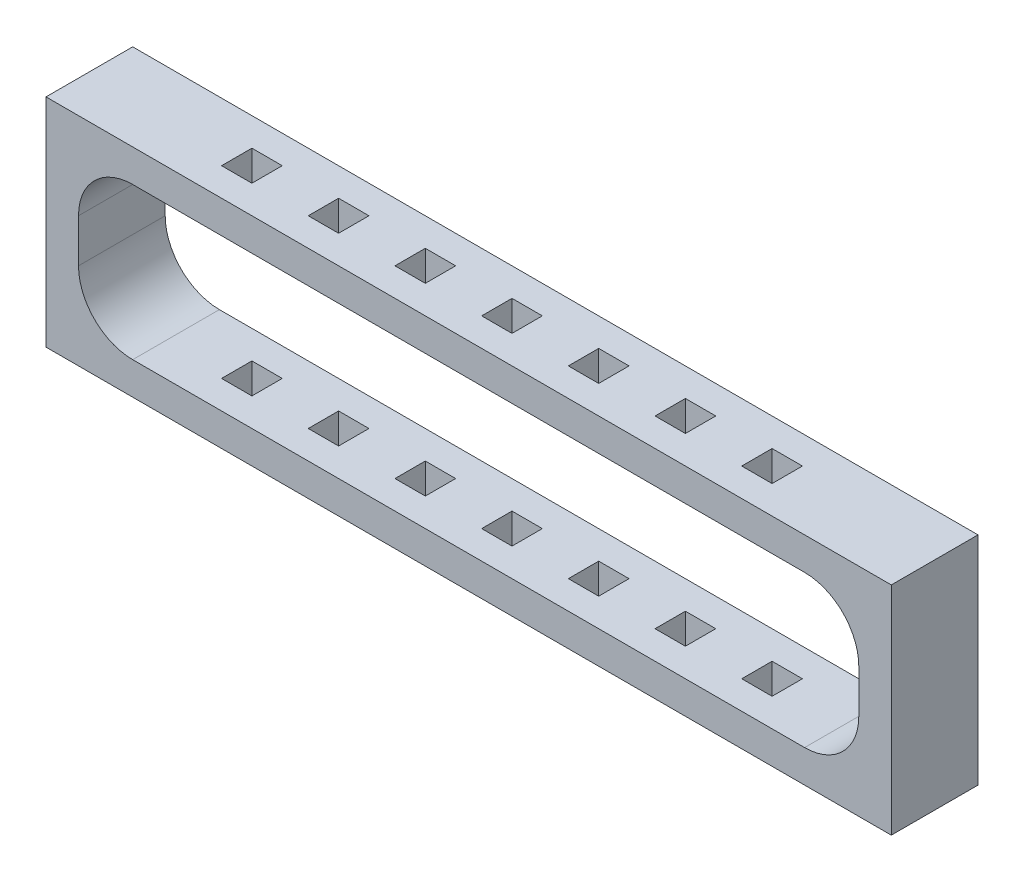
SolidWorks part; units mm, degrees
ref_plane "Plano frontal" through (0, 0, 0) normal (0, 0, 1) x (1, 0, 0)
ref_plane "Plano superior" through (0, 0, 0) normal (0, 1, 0) x (1, 0, 0)
ref_plane "Plano direito" through (0, 0, 0) normal (1, 0, 0) x (0, 0, -1)
sketch "Esboço1" plane through (0, 0, 0) normal (0, 0, 1) x (1, 0, 0)
  line L0 (-39, 0) -> (39, 0) construction
  line L1 (0, -10) -> (0, 10) construction
  line L2 (-39, 10) -> (39, 10)
  line L3 (39, 10) -> (39, -10)
  line L4 (0, -7) -> (0, 7) construction
  line L5 (-31, 7) -> (31, 7)
  line L6 (36, 2) -> (36, -2)
  line L7 (-36, 2) -> (-36, -2)
  line L8 (-39, 10) -> (-39, -10)
  line L9 (-31, -7) -> (31, -7)
  line L10 (-39, -10) -> (39, -10)
  arc A0 (31, 7) -> (36, 2) centre (31, 2) cw
  arc A1 (-31, 7) -> (-36, 2) centre (-31, 2) ccw
  arc A2 (-31, -7) -> (-36, -2) centre (-31, -2) cw
  arc A3 (31, -7) -> (36, -2) centre (31, -2) ccw
  point P14 (36, 0)
  point P18 (0, 0)
  point P25 (-36, 0)
  dimension "D3" = 5
  dimension "D1" = 39
  dimension "D2" = 10
  dimension "D4" = 36
extrude "Ressalto-extrusão1" add sketch "Esboço1" along normal blind 8
sketch "Esboço2" plane through (0, 10, 0) normal (0, 1, 0) x (1, 0, 0)
  line L0 (0, 0) -> (0, -8) construction
  line L1 (39, -8) -> (-39, -8) construction
  line L2 (-9.4, -2.6) -> (-6.6, -2.6)
  line L3 (-1.4, -2.6) -> (1.4, -2.6)
  line L4 (-1.4, -2.6) -> (-1.4, -5.4)
  line L5 (-1.4, -5.4) -> (1.4, -5.4)
  line L6 (1.4, -2.6) -> (1.4, -5.4)
  line L7 (-1.4, -2.6) -> (1.4, -5.4) construction
  line L8 (-1.4, -5.4) -> (1.4, -2.6) construction
  line L9 (-9.4, -2.6) -> (-9.4, -5.4)
  line L10 (-9.4, -5.4) -> (-6.6, -5.4)
  line L11 (-6.6, -2.6) -> (-6.6, -5.4)
  line L12 (-9.4, -2.6) -> (-6.6, -5.4) construction
  line L13 (-9.4, -5.4) -> (-6.6, -2.6) construction
  line L14 (-17.4, -2.6) -> (-14.6, -2.6)
  line L15 (-17.4, -2.6) -> (-17.4, -5.4)
  line L16 (-17.4, -5.4) -> (-14.6, -5.4)
  line L17 (-14.6, -2.6) -> (-14.6, -5.4)
  line L18 (-17.4, -2.6) -> (-14.6, -5.4) construction
  line L19 (-17.4, -5.4) -> (-14.6, -2.6) construction
  line L20 (-25.4, -2.6) -> (-22.6, -2.6)
  line L21 (-25.4, -2.6) -> (-25.4, -5.4)
  line L22 (-25.4, -5.4) -> (-22.6, -5.4)
  line L23 (-22.6, -2.6) -> (-22.6, -5.4)
  line L24 (-25.4, -2.6) -> (-22.6, -5.4) construction
  line L25 (-25.4, -5.4) -> (-22.6, -2.6) construction
  line L26 (25.4, -5.4) -> (22.6, -2.6) construction
  line L27 (25.4, -2.6) -> (22.6, -5.4) construction
  line L28 (17.4, -5.4) -> (14.6, -2.6) construction
  line L29 (17.4, -2.6) -> (14.6, -5.4) construction
  line L30 (9.4, -5.4) -> (6.6, -2.6) construction
  line L31 (9.4, -2.6) -> (6.6, -5.4) construction
  line L32 (22.6, -2.6) -> (22.6, -5.4)
  line L33 (25.4, -5.4) -> (22.6, -5.4)
  line L34 (25.4, -2.6) -> (25.4, -5.4)
  line L35 (25.4, -2.6) -> (22.6, -2.6)
  line L36 (14.6, -2.6) -> (14.6, -5.4)
  line L37 (17.4, -5.4) -> (14.6, -5.4)
  line L38 (17.4, -2.6) -> (17.4, -5.4)
  line L39 (17.4, -2.6) -> (14.6, -2.6)
  line L40 (6.6, -2.6) -> (6.6, -5.4)
  line L41 (9.4, -5.4) -> (6.6, -5.4)
  line L42 (9.4, -2.6) -> (9.4, -5.4)
  line L43 (9.4, -2.6) -> (6.6, -2.6)
  point P5 (0, -4)
  point P11 (-8, -4)
  point P16 (-16, -4)
  point P21 (-24, -4)
  point P37 (24, -4)
  point P38 (16, -4)
  point P39 (8, -4)
  dimension "D1" = 2.8
  dimension "D2" = 4
extrude "Corte-extrusão1" cut sketch "Esboço2" against normal through all
